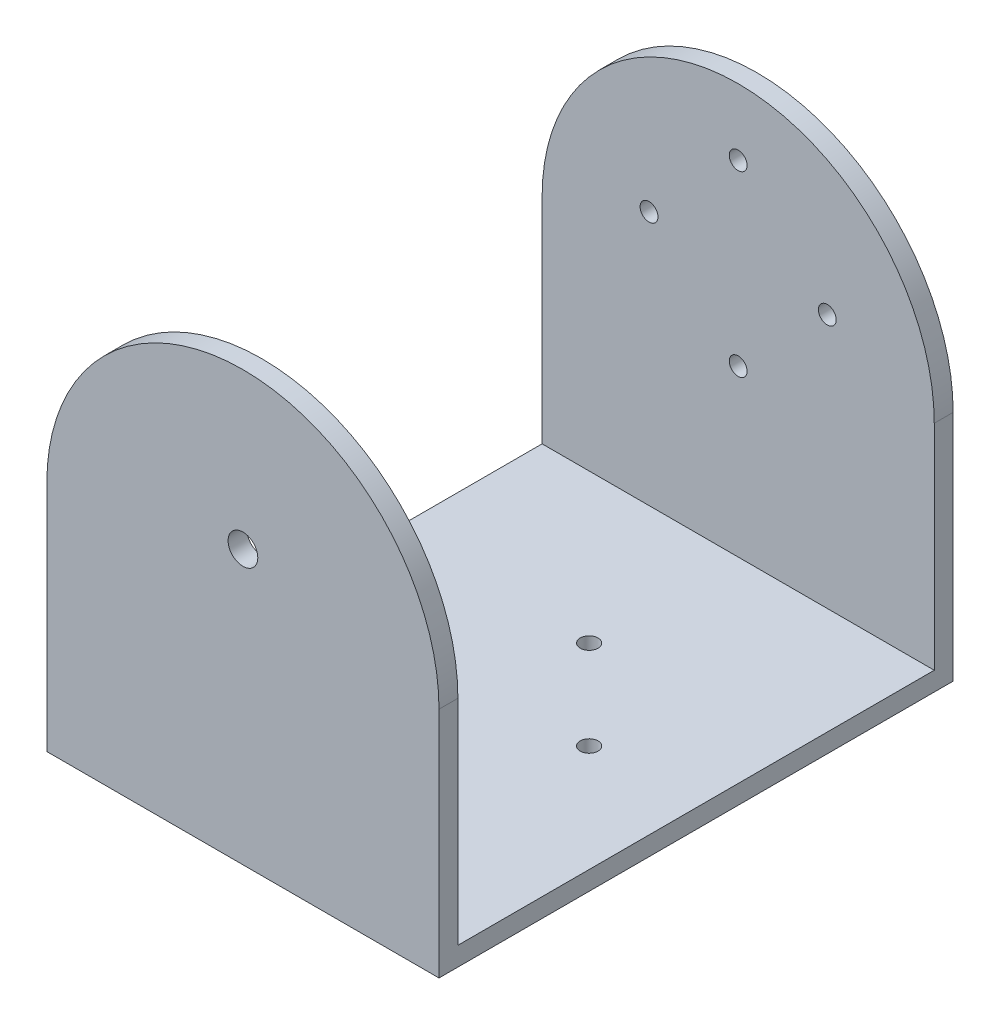
SolidWorks part; units mm, degrees
material "6061 Alloy"
ref_plane "Front Plane" through (0, 0, 0) normal (0, 0, 1) x (1, 0, 0)
ref_plane "Top Plane" through (0, 0, 0) normal (0, 1, 0) x (1, 0, 0)
ref_plane "Right Plane" through (0, 0, 0) normal (1, 0, 0) x (0, 0, -1)
sketch "Sketch1" plane through (0, 0, 0) normal (0, 1, 0) x (1, 0, 0)
  line L0 (-10.3213, 0) -> (10.2545, 0) construction
  line L1 (-16.5, 21.632) -> (16.5, 21.632)
  line L2 (-16.5, 21.632) -> (-16.5, -21.632)
  line L3 (-16.5, -21.632) -> (16.5, -21.632)
  line L4 (16.5, 21.632) -> (16.5, -21.632)
  line L5 (-16.5, 21.632) -> (16.5, -21.632) construction
  line L6 (-16.5, -21.632) -> (16.5, 21.632) construction
  line L7 (0, 8.8203) -> (0, -9.4436) construction
  circle A0 centre (0, 0) radius 12 construction
  circle A1 centre (0, 7.5) radius 0.75
  circle A2 centre (0, -7.5) radius 0.75
  circle A3 centre (7.5, 0) radius 0.75
  circle A4 centre (-7.5, 0) radius 0.75
  point P0 (0, 0)
  dimension "D1" = 24
  dimension "D6" = 1.5
  dimension "D2" = 7.5
  dimension "D3" = 15
  dimension "D4" = 7.5
  dimension "D5" = 15
  dimension "D7" = 43.264
  dimension "D8" = 33
extrude "Boss-Extrude1" add sketch "Sketch1" along normal blind 1.59
sketch "Sketch2" plane through (0, 1.59, 0) normal (0, 1, 0) x (1, 0, 0)
  line L0 (16.5, -21.632) -> (16.5, 21.632) construction
  line L1 (-16.5, 21.632) -> (16.5, 21.632)
  line L2 (-16.5, 21.632) -> (-16.5, 20.042)
  line L3 (-16.5, 20.042) -> (16.5, 20.042)
  line L4 (16.5, 21.632) -> (16.5, 20.042)
  line L6 (-16.5, -21.632) -> (16.5, -21.632)
  line L7 (-16.5, -21.632) -> (-16.5, -20.042)
  line L8 (-16.5, -20.042) -> (16.5, -20.042)
  line L9 (16.5, -21.632) -> (16.5, -20.042)
  dimension "D1" = 1.59
  dimension "D2" = 1.59
extrude "Boss-Extrude2" add sketch "Sketch2" along normal blind 18
sketch "Sketch3" plane through (0, 0, 21.632) normal (0, 0, 1) x (1, 0, 0)
  line L0 (-16.5, 19.59) -> (16.5, 19.59) construction
  line L1 (-16.5, 19.59) -> (-16.5, 0) construction
  line L2 (-16.5, 19.59) -> (16.5, 19.59)
  arc A0 (16.5, 19.59) -> (-16.5, 19.59) centre (0, 19.59) ccw
extrude "Boss-Extrude3" add sketch "Sketch3" against normal up to surface (1.59 mm away) up to face at (0, 10.59, 20.042)
sketch "Sketch4" plane through (0, 0, -21.632) normal (0, 0, -1) x (-1, 0, 0)
  line L0 (-16.5, 19.59) -> (16.5, 19.59) construction
  line L1 (-16.5, 19.59) -> (-16.5, 0) construction
  line L2 (-16.5, 19.59) -> (16.5, 19.59)
  arc A0 (16.5, 19.59) -> (-16.5, 19.59) centre (0, 19.59) ccw
extrude "Boss-Extrude4" add sketch "Sketch4" against normal up to surface (1.59 mm away) up to face at (0, 10.59, -20.042)
sketch "Sketch5" plane through (0, 0, 21.632) normal (0, 0, 1) x (1, 0, 0)
  circle A0 centre (0, 23) radius 1.25
  dimension "D2" = 2.5
  dimension "D1" = 23
extrude "Cut-Extrude1" cut sketch "Sketch5" against normal blind 6
sketch "Sketch6" plane through (0, 0, -21.632) normal (0, 0, -1) x (-1, 0, 0)
  circle A0 centre (0, 23) radius 7.5 construction
  circle A1 centre (0, 30.5) radius 0.75
  circle A2 centre (0, 15.5) radius 0.75
  circle A3 centre (7.5, 23) radius 0.75
  circle A4 centre (-7.5, 23) radius 0.75
  dimension "D2" = 15
  dimension "D3" = 1.5
  dimension "D1" = 23
extrude "Cut-Extrude2" cut sketch "Sketch6" against normal blind 6
